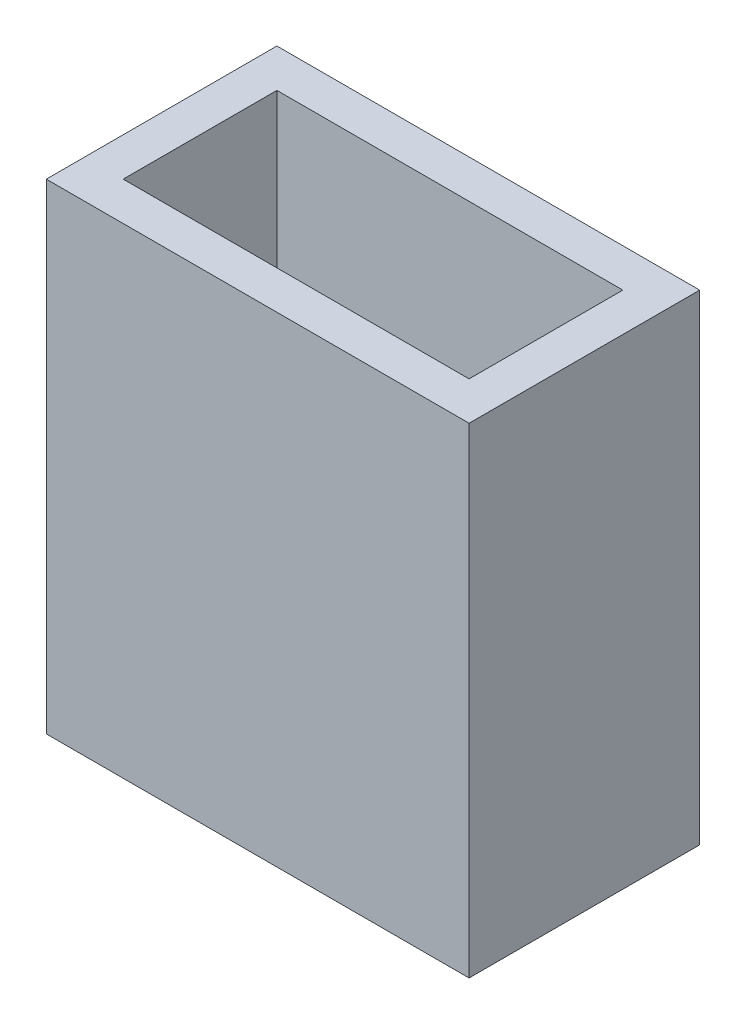
SolidWorks part; units mm, degrees
ref_plane "Front Plane" through (0, 0, 0) normal (0, 0, 1) x (1, 0, 0)
ref_plane "Top Plane" through (0, 0, 0) normal (0, 1, 0) x (1, 0, 0)
ref_plane "Right Plane" through (0, 0, 0) normal (1, 0, 0) x (0, 0, -1)
sketch "Sketch1" plane through (0, 0, 0) normal (0, 0, 1) x (1, 0, 0)
  line L1 (0, 0) -> (22, 0)
  line L2 (0, 0) -> (0, 25)
  line L3 (0, 25) -> (22, 25)
  line L4 (22, 0) -> (22, 25)
  dimension "D1" = 22
  dimension "D2" = 25
extrude "Boss-Extrude1" add sketch "Sketch1" along normal blind 12
sketch "Sketch2" plane through (0, 25, 0) normal (0, 1, 0) x (1, 0, 0)
  line L0 (0, -12) -> (0, 0) construction
  line L1 (2, -2) -> (20, -2)
  line L2 (2, -2) -> (2, -10)
  line L3 (2, -10) -> (20, -10)
  line L4 (20, -2) -> (20, -10)
  line L5 (22, -12) -> (22, 0) construction
  line L6 (22, 0) -> (0, 0) construction
  line L7 (22, -12) -> (0, -12) construction
  dimension "D1" = 2
  dimension "D2" = 2
  dimension "D3" = 2
  dimension "D4" = 2
extrude "Cut-Extrude1" cut sketch "Sketch2" against normal blind 25
equation "\"slider_h\"=25"
equation "\"D2@Sketch1\"=\"slider_h\""
equation "\"outer_thickness_slider\"=22"
equation "\"D1@Sketch1\"=\"outer_thickness_slider\""
equation "\"slider_thickness\"=12"
equation "\"D1@Boss-Extrude1\"=\"slider_thickness\""
equation "\"external_thickness_slider\"=2"
equation "\"D1@Sketch2\"=\"external_thickness_slider\""
equation "\"D2@Sketch2\"= \"external_thickness_slider\""
equation "\"D3@Sketch2\"= \"external_thickness_slider\""
equation "\"D4@Sketch2\"= \"external_thickness_slider\""
equation "\"D1@Cut-Extrude1\"= \"slider_h\""
